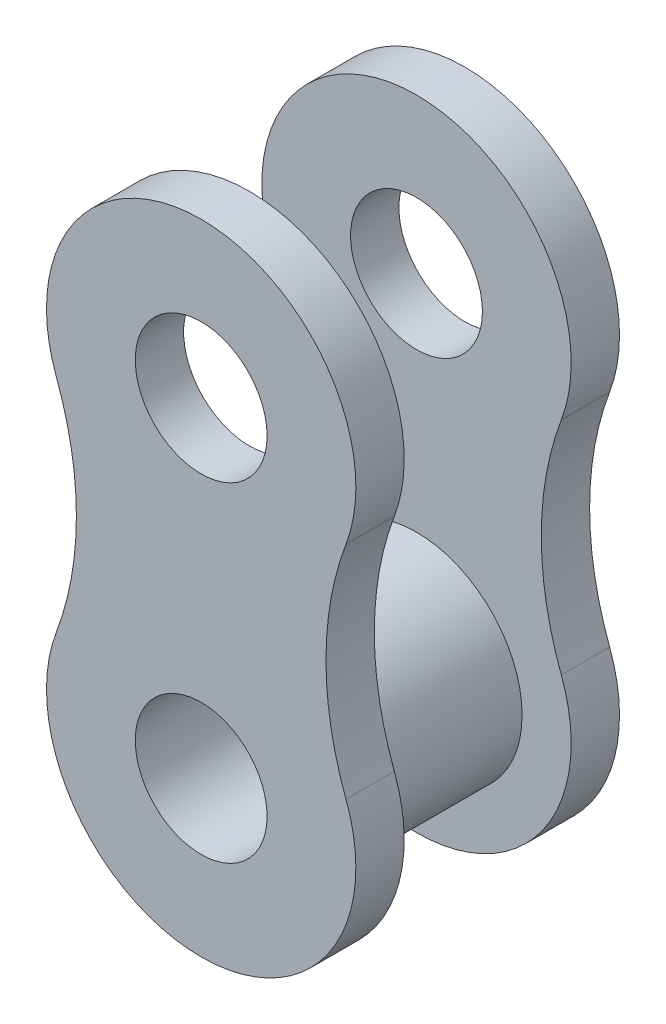
SolidWorks part; units mm, degrees
material "6061-T6 (SS)"
ref_plane "Front Plane" through (0, 0, 0) normal (0, 0, 1) x (1, 0, 0)
ref_plane "Top Plane" through (0, 0, 0) normal (0, 1, 0) x (1, 0, 0)
ref_plane "Right Plane" through (0, 0, 0) normal (1, 0, 0) x (0, 0, -1)
sketch "Sketch2" plane through (0, 0, 0) normal (0, 0, 1) x (1, 0, 0)
  line L0 (0, 0) -> (0, 9.525) construction
  line L1 (12.7, 4.7625) -> (-12.7, 4.7625) construction
  circle A0 centre (0, 0) radius 4.4704
  circle A1 centre (0, 9.525) radius 4.4704
  arc A2 (-4.1858, 1.5697) -> (-4.1858, 7.9553) centre (-12.7, 4.7625) ccw
  arc A3 (4.1858, 1.5697) -> (4.1858, 7.9553) centre (12.7, 4.7625) cw
  circle A4 centre (0, 9.525) radius 1.905
  circle A5 centre (0, 0) radius 1.905
  point P8 (0, 4.7625)
  dimension "D2" = 8.9408
  dimension "D4" = 3.81
  dimension "D1" = 9.525
  dimension "D3" = 25.4
extrude "Boss-Extrude1" add sketch "Sketch2" along normal blind 1.397 contours A0 A5 | A0 A3 A1 A2 | A1 A4
sketch "Sketch3" plane through (0, 0, 1.397) normal (0, 0, 1) x (1, 0, 0)
  circle A0 centre (0, 0) radius 3.0521
  circle A1 centre (0, 0) radius 1.905
extrude "Boss-Extrude2" add sketch "Sketch3" along normal blind 4.826
ref_plane "Plane1" through (0, 0, 3.81) normal (0, 0, 1) x (1, 0, 0)
mirror "Mirror1" about plane through (0, 0, 3.81) normal (0, 0, 1) of "Boss-Extrude1"
